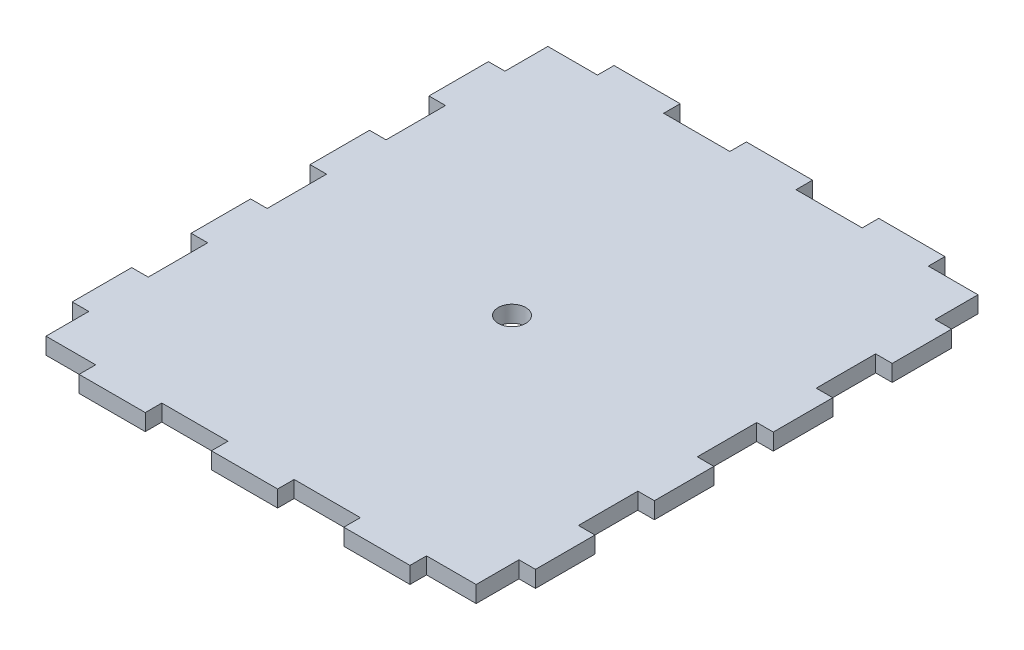
SolidWorks part; units mm, degrees
material "Balsa"
ref_plane "Front" through (0, 0, 0) normal (0, 0, 1) x (1, 0, 0)
ref_plane "Top" through (0, 0, 0) normal (0, 1, 0) x (1, 0, 0)
ref_plane "Right" through (0, 0, 0) normal (1, 0, 0) x (0, 0, -1)
sketch "Esboço1" plane through (0, 0, 0) normal (0, 1, 0) x (1, 0, 0)
  line L1 (-42, -48.5) -> (42, -48.5)
  line L2 (-42, -48.5) -> (-42, 48.5)
  line L3 (-42, 48.5) -> (42, 48.5)
  line L4 (42, -48.5) -> (42, 48.5)
  line L5 (-42, -48.5) -> (42, 48.5) construction
  line L6 (-42, 48.5) -> (42, -48.5) construction
  point P0 (0, 0)
  dimension "D1" = 84
  dimension "D2" = 97
extrude "Ressalto-extrusão1" add sketch "Esboço1" along normal blind 3
sketch "Esboço2" plane through (0, 0, 0) normal (0, -1, 0) x (1, 0, 0)
  line L1 (-42, -48.5) -> (-39, -48.5)
  line L2 (-42, -48.5) -> (-42, -37.7222)
  line L3 (-42, -37.7222) -> (-39, -37.7222)
  line L4 (-39, -48.5) -> (-39, -37.7222)
  line L6 (39, -48.5) -> (42, -48.5)
  line L7 (39, -48.5) -> (39, -37.7222)
  line L8 (39, -37.7222) -> (42, -37.7222)
  line L9 (42, -48.5) -> (42, -37.7222)
  line L10 (39, -26.94) -> (42, -26.94)
  line L11 (39, -26.94) -> (39, -16.1622)
  line L12 (39, -16.1622) -> (42, -16.1622)
  line L13 (42, -26.94) -> (42, -16.1622)
  line L14 (39, -5.38) -> (42, -5.38)
  line L15 (39, -5.38) -> (39, 5.3978)
  line L16 (39, 5.3978) -> (42, 5.3978)
  line L17 (42, -5.38) -> (42, 5.3978)
  line L18 (39, 16.18) -> (42, 16.18)
  line L19 (39, 16.18) -> (39, 26.9578)
  line L20 (39, 26.9578) -> (42, 26.9578)
  line L21 (42, 16.18) -> (42, 26.9578)
  line L22 (39, 37.74) -> (42, 37.74)
  line L23 (39, 37.74) -> (39, 48.5178)
  line L24 (39, 48.5178) -> (42, 48.5178)
  line L25 (42, 37.74) -> (42, 48.5178)
  line L26 (-42, -26.94) -> (-39, -26.94)
  line L27 (-42, -26.94) -> (-42, -16.1622)
  line L28 (-42, -16.1622) -> (-39, -16.1622)
  line L29 (-39, -26.94) -> (-39, -16.1622)
  line L30 (-42, -5.38) -> (-39, -5.38)
  line L31 (-42, -5.38) -> (-42, 5.3978)
  line L32 (-42, 5.3978) -> (-39, 5.3978)
  line L33 (-39, -5.38) -> (-39, 5.3978)
  line L34 (-42, 16.18) -> (-39, 16.18)
  line L35 (-42, 16.18) -> (-42, 26.9578)
  line L36 (-42, 26.9578) -> (-39, 26.9578)
  line L37 (-39, 16.18) -> (-39, 26.9578)
  line L38 (-42, 37.74) -> (-39, 37.74)
  line L39 (-42, 37.74) -> (-42, 48.5178)
  line L40 (-42, 48.5178) -> (-39, 48.5178)
  line L41 (-39, 37.74) -> (-39, 48.5178)
  dimension "D1" = 3
  dimension "D2" = 10.7778
  dimension "D3" = 2
  dimension "D4" = 5
extrude "Corte-extrusão4" cut sketch "Esboço2" against normal blind 3
sketch "Esboço5" plane through (0, 0, 0) normal (0, 1, 0) x (1, 0, 0)
  line L0 (-42, 45.5) -> (-42, 48.5)
  line L1 (-42, -48.5) -> (-30, -48.5)
  line L2 (-42, -48.5) -> (-42, -45.5)
  line L3 (-42, 48.5) -> (-30, 48.5)
  line L4 (42, -48.5) -> (42, -45.5)
  line L8 (42, 45.5) -> (42, 48.5)
  line L9 (-42, -45.5) -> (-30, -45.5)
  line L10 (-30, -48.5) -> (-30, -45.5)
  line L11 (-18, -48.5) -> (-18, -45.5)
  line L12 (-18, -45.5) -> (-6, -45.5)
  line L13 (-6, -48.5) -> (-6, -45.5)
  line L14 (30, -48.5) -> (42, -48.5)
  line L15 (6, -48.5) -> (6, -45.5)
  line L16 (6, -45.5) -> (18, -45.5)
  line L17 (18, -48.5) -> (18, -45.5)
  line L18 (6, -48.5) -> (18, -48.5)
  line L19 (30, -48.5) -> (30, -45.5)
  line L20 (30, -45.5) -> (42, -45.5)
  line L21 (-18, -48.5) -> (-6, -48.5)
  line L22 (-18, 45.5) -> (-6, 45.5)
  line L23 (-18, 45.5) -> (-18, 48.5)
  line L24 (-18, 48.5) -> (-6, 48.5)
  line L25 (-6, 45.5) -> (-6, 48.5)
  line L26 (6, 45.5) -> (18, 45.5)
  line L27 (6, 45.5) -> (6, 48.5)
  line L28 (6, 48.5) -> (18, 48.5)
  line L29 (18, 45.5) -> (18, 48.5)
  line L30 (30, 45.5) -> (42, 45.5)
  line L31 (30, 45.5) -> (30, 48.5)
  line L32 (30, 48.5) -> (42, 48.5)
  line L34 (-42, 45.5) -> (-30, 45.5)
  line L37 (-30, 45.5) -> (-30, 48.5)
  line L42 (-42, 48.5) -> (-30, 48.5) [skipped]
  line L43 (30, 48.5) -> (42, 48.5) [skipped]
  line L44 (6, 48.5) -> (18, 48.5) [skipped]
  line L45 (-18, 48.5) -> (-6, 48.5) [skipped]
  line L46 (42, 45.5) -> (42, 48.5) [skipped]
  line L47 (42, -48.5) -> (42, -45.5) [skipped]
  point P0 (0, 0)
  dimension "D1" = 84
  dimension "D2" = 97
  dimension "D3" = 3
  dimension "D4" = 12
  dimension "D5" = 4
  dimension "D6" = 2
extrude "Corte-extrusão9" cut sketch "Esboço5" along normal up to next
sketch "Esboço6" plane through (0, 0, 0) normal (0, -1, 0) x (1, 0, 0)
  circle A0 centre (0, 0) radius 2.5
extrude "Corte-extrusão10" cut sketch "Esboço6" against normal up to next
